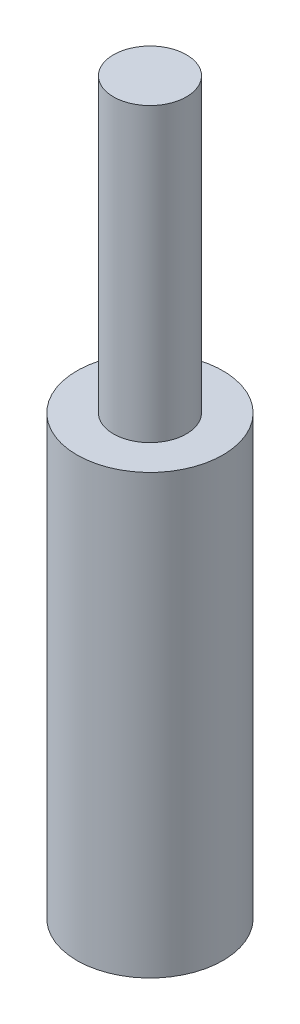
SolidWorks part; units mm, degrees
ref_plane "Front Plane" through (0, 0, 0) normal (0, 0, 1) x (1, 0, 0)
ref_plane "Top Plane" through (0, 0, 0) normal (0, 1, 0) x (1, 0, 0)
ref_plane "Right Plane" through (0, 0, 0) normal (1, 0, 0) x (0, 0, -1)
sketch "Sketch1" plane through (0, 0, 0) normal (0, 1, 0) x (1, 0, 0)
  circle A0 centre (0, 0) radius 1
extrude "Boss-Extrude1" add sketch "Sketch1" along normal blind 6
sketch "Sketch2" plane through (0, 6, 0) normal (0, 1, 0) x (1, 0, 0)
  circle A0 centre (0, 0) radius 0.5
extrude "Boss-Extrude2" add sketch "Sketch2" along normal blind 4
